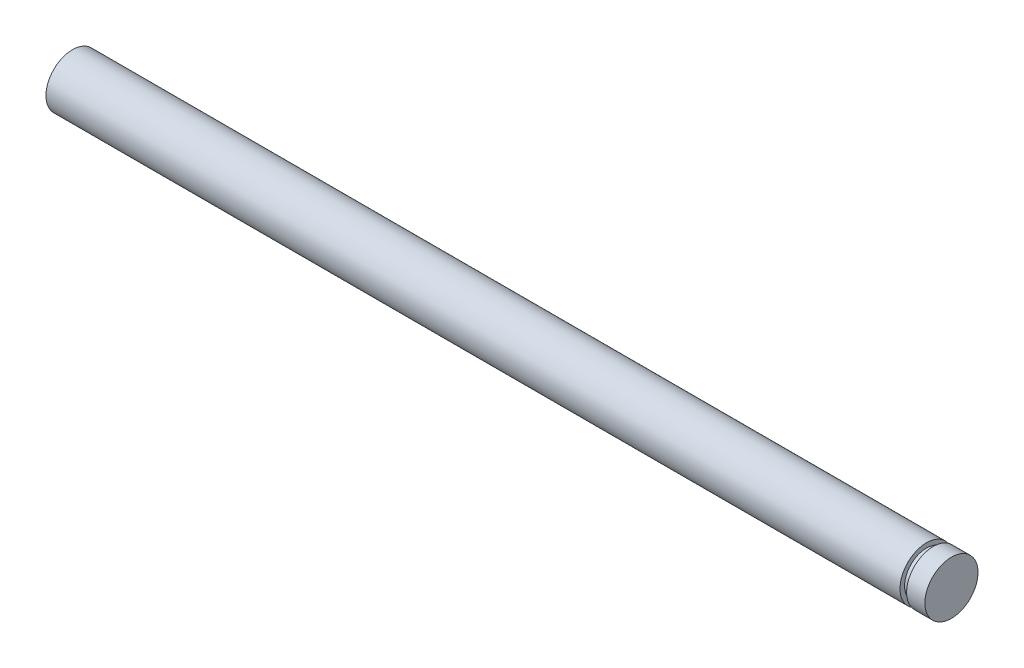
SolidWorks part; units mm, degrees
ref_plane "Front Plane" through (0, 0, 0) normal (0, 0, 1) x (1, 0, 0)
ref_plane "Top Plane" through (0, 0, 0) normal (0, 1, 0) x (1, 0, 0)
ref_plane "Right Plane" through (0, 0, 0) normal (1, 0, 0) x (0, 0, -1)
sketch "Sketch1" plane through (0, 0, 0) normal (0, 0, 1) x (1, 0, 0)
  line L0 (0, 0) -> (0, 0.725)
  line L1 (0, 0.725) -> (23.32, 0.725)
  line L2 (23.32, 0.725) -> (23.32, 0.6)
  line L3 (23.32, 0.6) -> (23.5, 0.6)
  line L4 (23.5, 0.6) -> (23.5, 0.725)
  line L5 (23.5, 0.725) -> (24, 0.725)
  line L6 (24, 0.725) -> (24, 0)
  line L7 (24, 0) -> (0, 0) construction
  line L8 (0, 0) -> (24, 0)
  point P7 (22.0518, 0.5283)
  dimension "D1" = 24
  dimension "D2" = 0.725
  dimension "D3" = 0.6
  dimension "D4" = 0.5
  dimension "D5" = 0.18
revolve "Revolve1" add sketch "Sketch1" angle 360 about L7
